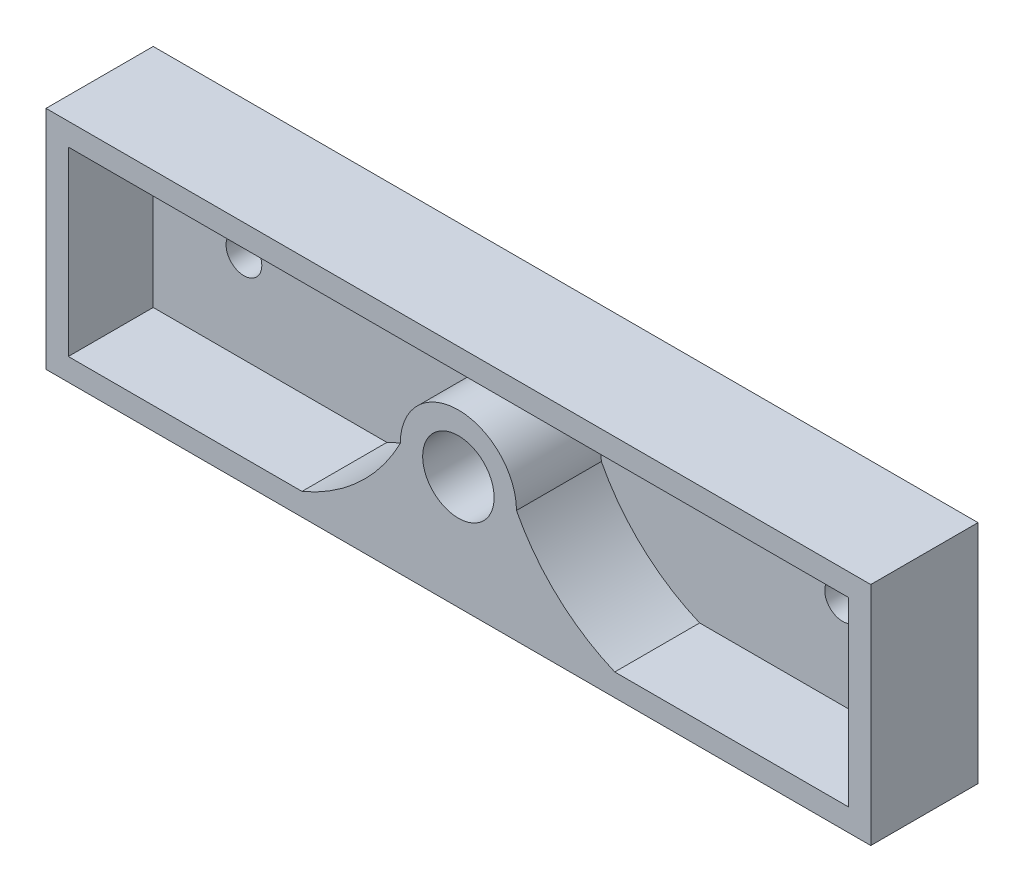
SolidWorks part; units mm, degrees
material "6061-T6 (SS)"
ref_plane "Front" through (0, 0, 0) normal (0, 0, 1) x (1, 0, 0)
ref_plane "Top" through (0, 0, 0) normal (0, 1, 0) x (1, 0, 0)
ref_plane "Right" through (0, 0, 0) normal (1, 0, 0) x (0, 0, -1)
sketch "Croquis2" plane through (0, 0, 0) normal (0, 0, 1) x (1, 0, 0)
  line L1 (0, 0) -> (92.3, 0)
  line L2 (0, 0) -> (0, 25.3)
  line L3 (0, 25.3) -> (92.3, 25.3)
  line L4 (92.3, 0) -> (92.3, 25.3)
  dimension "D1" = 25.3
  dimension "D2" = 92.3
extrude "Saliente-Extruir1" add sketch "Croquis2" along normal blind 12
shell "Vaciado1" thickness 2.5
sketch "Croquis3" plane through (0, 0, 2.5) normal (0, 0, 1) x (1, 0, 0)
  line L0 (2.5, 12.65) -> (89.8, 12.65) construction
  line L1 (2.5, 22.8) -> (2.5, 2.5) construction
  line L2 (89.8, 2.5) -> (89.8, 22.8) construction
  line L3 (2.5, 2.5) -> (89.8, 2.5) construction
  line L4 (2.5, 22.8) -> (22.8, 22.8) construction
  line L5 (2.5, 22.8) -> (2.5, 2.5) construction
  line L6 (2.5, 2.5) -> (22.8, 2.5) construction
  line L7 (22.8, 22.8) -> (22.8, 2.5) construction
  line L8 (12.65, 22.8) -> (12.65, 2.5) construction
  line L9 (0, 0) -> (92.3, 0) construction
  circle A2 centre (46.15, 12.65) radius 4
  circle A3 centre (12.65, 12.65) radius 2
  circle A4 centre (79.65, 12.65) radius 2
  dimension "D1" = 20.3
  dimension "D2" = 8
  dimension "D3" = 4
  dimension "D4" = 33.5
  dimension "D5" = 10.15
  dimension "D6" = 12.65
extrude "Cortar-Extruir1" cut sketch "Croquis3" against normal blind 12
sketch "Croquis5" plane through (0, 0, 2.5) normal (0, 0, 1) x (1, 0, 0)
  line L0 (2.5, 2.5) -> (89.8, 2.5) construction
  line L1 (46.15, 12.65) -> (46.15, 28.7357) construction
  line L2 (28.65, 2.5) -> (63.65, 2.5)
  circle A0 centre (46.15, 12.65) radius 4
  circle A1 centre (46.15, 12.65) radius 4 construction
  arc A2 (52.65, 12.65) -> (39.65, 12.65) centre (46.15, 12.65) ccw
  arc A3 (52.65, 12.65) -> (63.65, 2.5) centre (72.1502, 22.7477) ccw
  arc A4 (39.65, 12.65) -> (28.65, 2.5) centre (20.1498, 22.7477) cw
  dimension "D1" = 35
  dimension ".25" = 2.5
extrude "Saliente-Extruir2" add sketch "Croquis5" along normal up to surface (9.5 mm away) up to face at (46.15, 12.65, 12)
